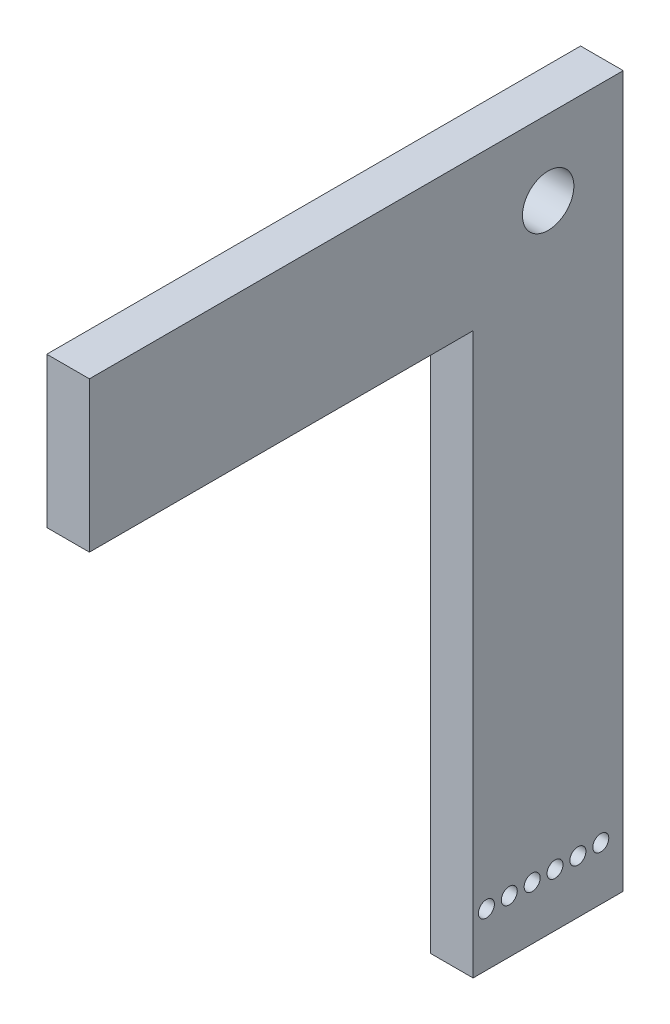
SolidWorks part; units mm, degrees
material "Hardboard"
ref_plane "Front Plane" through (0, 0, 0) normal (0, 0, 1) x (1, 0, 0)
ref_plane "Top Plane" through (0, 0, 0) normal (0, 1, 0) x (1, 0, 0)
ref_plane "Right Plane" through (0, 0, 0) normal (1, 0, 0) x (0, 0, -1)
sketch "Sketch1" plane through (0, 0, 0) normal (1, 0, 0) x (0, 0, -1)
  line L0 (-43.0322, 7.0419) -> (7.0419, 7.0419)
  line L1 (7.0419, 7.0419) -> (7.0419, -59.6273)
  line L2 (7.0419, -59.6273) -> (-7.0419, -59.6273)
  line L3 (-7.0419, -59.6273) -> (-7.0419, -7.0419)
  line L4 (-7.0419, -7.0419) -> (-43.0322, -7.0419)
  line L5 (-43.0322, -7.0419) -> (-43.0322, 7.0419)
  line L6 (-7.0419, -7.0419) -> (7.0419, 7.0419) construction
  circle A0 centre (0, 0) radius 2.413
  circle A1 centre (-5.7919, -54.6273) radius 0.75
  circle A2 centre (-3.6465, -54.6273) radius 0.75
  circle A3 centre (-1.501, -54.6273) radius 0.75
  circle A4 centre (0.6444, -54.6273) radius 0.75
  circle A5 centre (2.7899, -54.6273) radius 0.75
  circle A6 centre (4.9353, -54.6273) radius 0.75
  dimension "D1" = 4.826
  dimension "D2" = 1.5
  dimension "D3" = 1.25
  dimension "D4" = 5
  dimension "D5" = 6
extrude "Boss-Extrude1" add sketch "Sketch1" along normal mid plane 4
